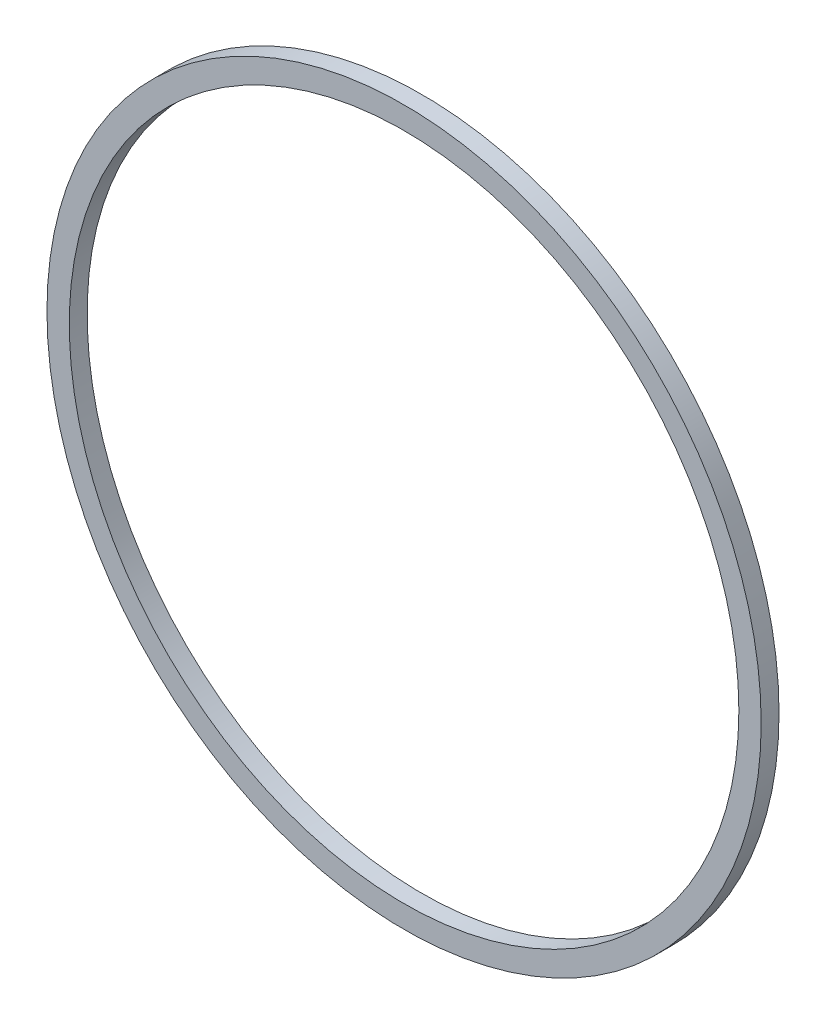
SolidWorks part; units mm, degrees
ref_plane "Front Plane" through (0, 0, 0) normal (0, 0, 1) x (1, 0, 0)
ref_plane "Top Plane" through (0, 0, 0) normal (0, 1, 0) x (1, 0, 0)
ref_plane "Right Plane" through (0, 0, 0) normal (1, 0, 0) x (0, 0, -1)
sketch "Sketch1" plane through (0, 0, 0) normal (0, 0, 1) x (1, 0, 0)
  circle A0 centre (0, 0) radius 37.5
  circle A1 centre (0, 0) radius 40
  dimension "D1" = 75
  dimension "D2" = 80
extrude "Boss-Extrude3" add sketch "Sketch1" along normal blind 2 contours A0 | A1
